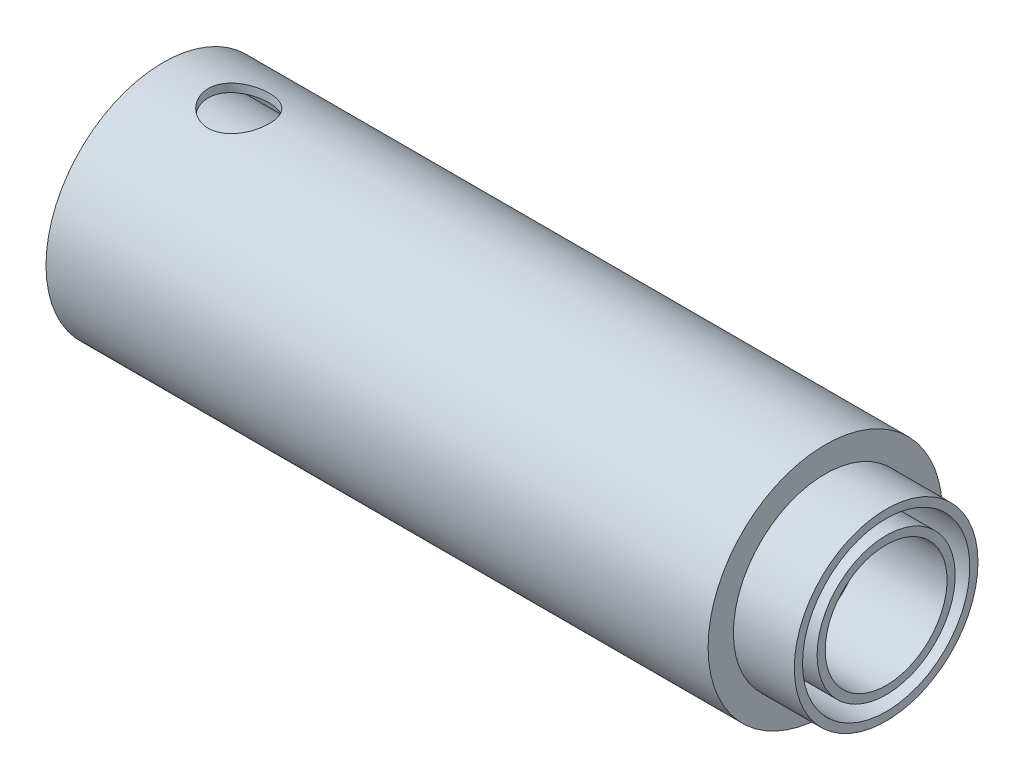
SolidWorks part; units mm, degrees
ref_plane "Front Plane" through (0, 0, 0) normal (0, 0, 1) x (1, 0, 0)
ref_plane "Top Plane" through (0, 0, 0) normal (0, 1, 0) x (1, 0, 0)
ref_plane "Right Plane" through (0, 0, 0) normal (1, 0, 0) x (0, 0, -1)
sketch "Sketch2" plane through (0, 0, 0) normal (0, 0, 1) x (1, 0, 0)
  line L0 (0.0787, 26.4677) -> (0.0787, 36.6277)
  line L1 (0.0787, 36.6277) -> (207.0887, 36.6277)
  line L2 (5.1629, 34.0877) -> (5.1629, 29.0077)
  line L3 (5.1629, 34.0877) -> (204.5487, 34.0877)
  line L4 (5.1629, 29.0077) -> (127, 29.0077)
  line L5 (13.1386, 0.0596) -> (13.1386, 21.6496)
  line L13 (226.1387, 19.05) -> (226.1387, 21.59)
  line L14 (226.1387, 26.162) -> (226.1387, 28.7163)
  line L15 (0.0787, 26.4677) -> (199.4687, 26.4677)
  line L20 (0, 0) -> (171.7932, 0)
  line L21 (19.6906, 0.0894) -> (19.6906, 36.6277)
  line L22 (19.6906, 0.0894) -> (19.6906, -36.4866)
  line L23 (19.6906, 29.0077) -> (19.6906, 0.0894)
  line L24 (199.4687, 26.4677) -> (199.4687, 19.05)
  line L25 (127, 29.0077) -> (202.0087, 29.0077)
  line L26 (202.0087, 29.0077) -> (202.0087, 21.59)
  line L27 (199.4687, 19.05) -> (226.1387, 19.05)
  line L28 (202.0087, 21.59) -> (226.1387, 21.59)
  line L30 (204.5487, 34.0877) -> (204.5487, 26.162)
  line L31 (207.0887, 36.6277) -> (207.0887, 28.7163)
  line L32 (207.0887, 28.7163) -> (226.1387, 28.7163)
  line L33 (204.5487, 26.162) -> (226.1387, 26.162)
  dimension "D1" = 2.54
  dimension "D2" = 207.01
  dimension "D3" = 19.05
  dimension "D4" = 2.54
  dimension "D5" = 5.08
  dimension "D6" = 2.54
  dimension "D7" = 26.162
  dimension "D8" = 2.5543
  dimension "D9" = 2.54
  dimension "D10" = 2.54
  dimension "D11" = 2.54
  dimension "D12" = 19.05
  dimension "D13" = 26.67
revolve "Revolve2" add sketch "Sketch2" angle 360 about L20
ref_plane "Plane1" through (0, 36.6277, 0) normal (0, 1, 0) x (1, 0, 0)
ref_plane "Plane2" through (0, -36.6277, 0) normal (0, 1, 0) x (1, 0, 0)
sketch "Sketch9" plane through (0, 36.6277, 0) normal (0, 1, 0) x (1, 0, 0)
  line L0 (0, 0) -> (171.7932, 0) construction
  circle A0 centre (23.7189, 0) radius 9.525
sketch "Sketch10" plane through (0, -36.6277, 0) normal (0, 1, 0) x (1, 0, 0)
  circle A0 centre (23.7189, 0) radius 9.525
extrude "Cut-Extrude9" cut sketch "Sketch9" against normal blind 5.842 contours A0
extrude "Cut-Extrude10" cut sketch "Sketch10" along normal blind 15.24 contours A0
